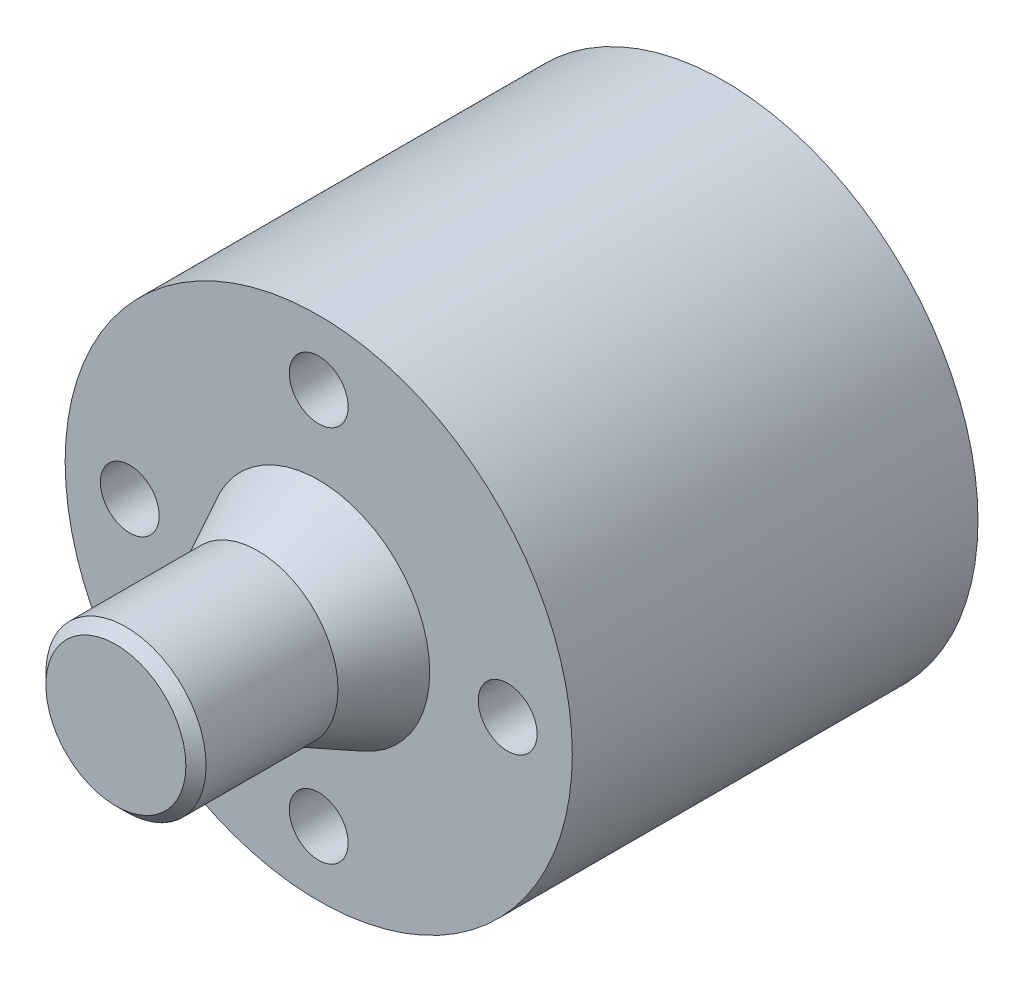
SolidWorks part; units mm, degrees
ref_plane "Front Plane" through (0, 0, 0) normal (0, 0, 1) x (1, 0, 0)
ref_plane "Top Plane" through (0, 0, 0) normal (0, 1, 0) x (1, 0, 0)
ref_plane "Right Plane" through (0, 0, 0) normal (1, 0, 0) x (0, 0, -1)
sketch "Sketch1" plane through (0, 0, 0) normal (0, 0, 1) x (1, 0, 0)
  circle A0 centre (0, 0) radius 12.5
  dimension "D2" = 25
extrude "Boss-Extrude1" add sketch "Sketch1" along normal mid plane 15
sketch "Sketch10" plane through (0, 0, 7.5) normal (0, 0, 1) x (1, 0, 0)
  circle A0 centre (0, 0) radius 12.5
  dimension "D1" = 25
sketch "Sketch8" plane through (0, 0, 7.5) normal (0, 0, 1) x (1, 0, 0)
  line L2 (-6.125, 6.125) -> (6.125, 6.125)
  line L3 (-6.125, 6.125) -> (-6.125, -6.125)
  line L4 (-6.125, -6.125) -> (6.125, -6.125)
  line L5 (6.125, 6.125) -> (6.125, -6.125)
  line L6 (-6.125, 6.125) -> (6.125, -6.125) construction
  line L7 (-6.125, -6.125) -> (6.125, 6.125) construction
  point P5 (0, 0)
  point P14 (0, 0)
  dimension "D1" = 12.25
extrude "Cut-Extrude1" cut sketch "Sketch8" against normal up to next
sketch "Sketch11" plane through (0, 0, 7.5) normal (0, 0, 1) x (1, 0, 0)
  line L0 (6.125, -6.125) -> (6.125, 6.125) construction
  circle A0 centre (9.315, 0) radius 1.45
  circle A1 centre (0, -9.315) radius 1.45
  circle A2 centre (-9.315, 0) radius 1.45
  circle A3 centre (0, 9.315) radius 1.45
  point P13 (0, 0)
  dimension "D1" = 2.9
  dimension "D2" = 3.19
  dimension "D3" = 4
extrude "Cut-Extrude4" cut sketch "Sketch11" against normal through all
sketch "Sketch14" plane through (0, 0, 7.5) normal (0, 0, 1) x (1, 0, 0)
  circle A0 centre (0, 0) radius 12.5
  circle A1 centre (0, 0) radius 12.5 construction
extrude "Boss-Extrude2" add sketch "Sketch14" along normal blind 5
sketch "Sketch13" plane through (0, 0, 0) normal (0, 1, 0) x (1, 0, 0)
  line L0 (0, -11.9651) -> (0, -27.8724) construction
  line L1 (0, -15.5) -> (3.95, -15.5)
  line L2 (-12.5, -12.5) -> (12.5, -12.5) construction
  line L3 (3.95, -15.5) -> (7.5, -8.5067)
  line L4 (7.5, -8.5067) -> (0, -8.5067)
  line L5 (0, -8.5067) -> (0, -15.5)
  dimension "D1" = 3.95
  dimension "D2" = 3
  dimension "D3" = 7.5
revolve "Revolve1" add sketch "Sketch13" angle 360 about L0
sketch "Sketch15" plane through (0, 0, 15.5) normal (0, 0, 1) x (1, 0, 0)
  circle A0 centre (0, 0) radius 3.95
extrude "Boss-Extrude3" add sketch "Sketch15" along normal blind 7
chamfer "Chamfer1" distance 0.5 angle 45 1 edges at (3.95, 0, 22.5)
sketch "Sketch18" plane through (0, 0, 12.5) normal (0, 0, 1) x (1, 0, 0)
  circle A0 centre (-9.315, 0) radius 1.45
  circle A1 centre (0, -9.315) radius 1.45
  circle A2 centre (9.315, 0) radius 1.45
  circle A3 centre (0, 9.315) radius 1.45
extrude "Cut-Extrude6" cut sketch "Sketch18" against normal blind 30
equation "\"drumDiameter\"= 25"
equation "\"D2@Sketch1\"= \"drumDiameter\""
equation "\"drumLength\"=15"
equation "\"foamThickness\"= 5"
equation "\"drumAbove\"= 0.6"
equation "\"holderThicc\"= 2"
equation "\"D1@Boss-Extrude1\"=\"drumLength\""
equation "\"squareBarLength\"= 12.25"
equation "\"D1@Sketch8\"=\"squareBarLength\""
equation "\"D1@Sketch10\"=\"drumDiameter\""
equation "\"toothlen\"= 2.5"
